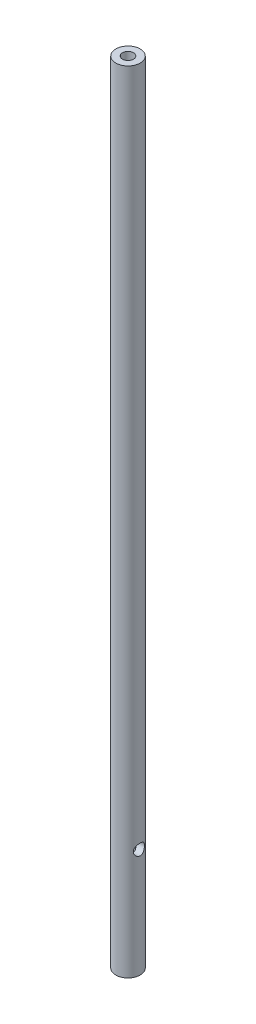
SolidWorks part; units mm, degrees
ref_plane "Front Plane" through (0, 0, 0) normal (0, 0, 1) x (1, 0, 0)
ref_plane "Top Plane" through (0, 0, 0) normal (0, 1, 0) x (1, 0, 0)
ref_plane "Right Plane" through (0, 0, 0) normal (1, 0, 0) x (0, 0, -1)
sketch "Sketch1" plane through (0, 0, 0) normal (0, 1, 0) x (1, 0, 0)
  circle A0 centre (0, 0) radius 5.5
  dimension "D1" = 11
extrude "Boss-Extrude2" add sketch "Sketch1" along normal mid plane 355.6
sketch "Sketch4" plane through (0, 177.8, 0) normal (0, 1, 0) x (1, 0, 0)
  circle A0 centre (0, 0) radius 2.5
  circle A1 centre (0, 0) radius 5.5 construction
  dimension "D1" = 5
extrude "Cut-Extrude1" cut sketch "Sketch4" against normal through all
ref_plane "Plane2" through (10, 0, 0) normal (1, 0, 0) x (0, 0, -1)
sketch "Sketch7" plane through (10, 0, 0) normal (1, 0, 0) x (0, 0, -1)
  line L1 (0, 177.8) -> (0, -177.8) construction
  circle A0 centre (0, -128.8) radius 2.5
  point P7 (0, 0)
  dimension "D1" = 5
  dimension "D2" = 49
extrude "Cut-Extrude3" cut sketch "Sketch7" against normal up to next
